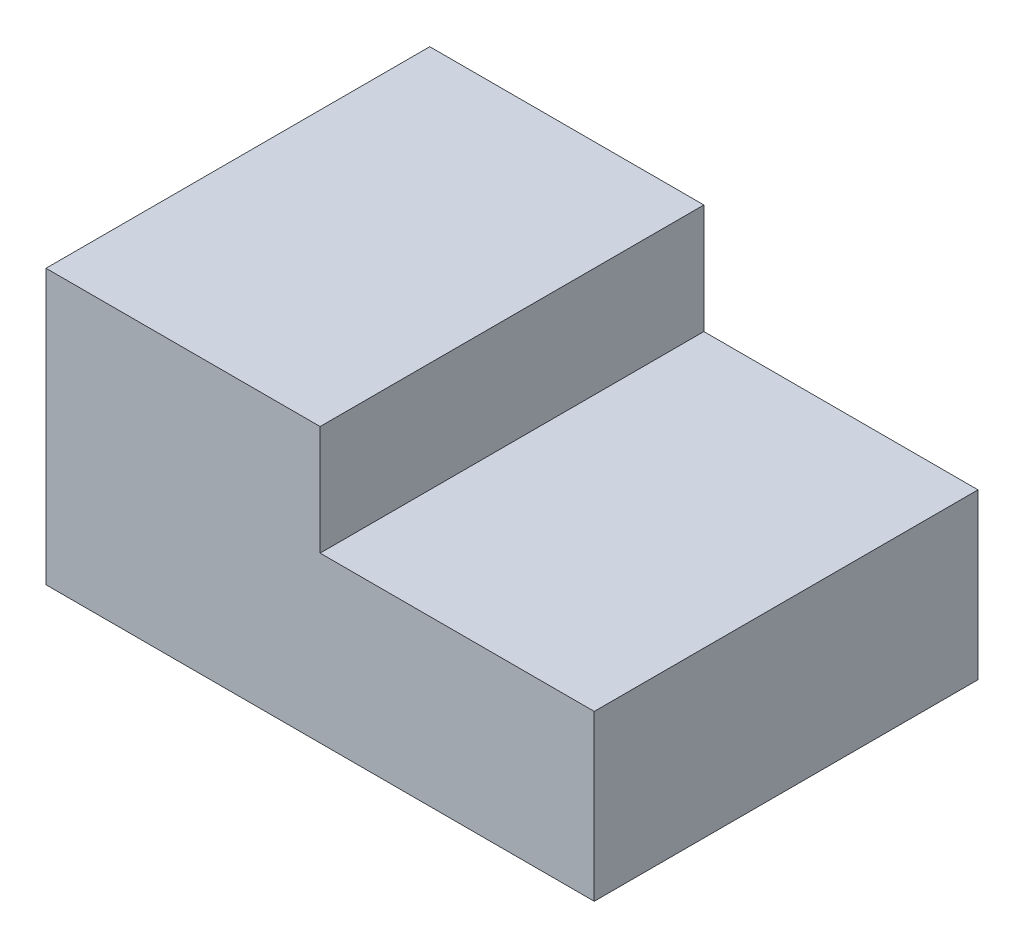
SolidWorks part; units mm, degrees
ref_plane "前视基准面" through (0, 0, 0) normal (0, 0, 1) x (1, 0, 0)
ref_plane "上视基准面" through (0, 0, 0) normal (0, 1, 0) x (1, 0, 0)
ref_plane "右视基准面" through (0, 0, 0) normal (1, 0, 0) x (0, 0, -1)
other "Configuration Table"
sketch "草图1" plane through (0, 0, 0) normal (0, 0, 1) x (1, 0, 0)
  line L0 (0, 0) -> (10, 0)
  line L1 (10, 0) -> (10, 3)
  line L2 (10, 3) -> (5, 3)
  line L3 (5, 3) -> (5, 5)
  line L4 (5, 5) -> (0, 5)
  line L5 (0, 5) -> (0, 0)
  dimension "D1" = 10
  dimension "D2" = 3
  dimension "D3" = 5
  dimension "D4" = 2
extrude "凸台-拉伸1" add sketch "草图1" along normal mid plane 7
sketch "草图2" plane through (0, 0, 0) normal (-1, 0, 0) x (0, 0, 1)
  line L0 (0, 0) -> (0, 2.5) construction
  line L1 (1.6, 4.1) -> (1.6, 0.9)
  line L2 (1.6, 4.1) -> (-1.6, 4.1)
  line L3 (1.6, 0.9) -> (-1.6, 0.9)
  line L4 (-1.6, 4.1) -> (-1.6, 0.9)
  line L5 (1.6, 4.1) -> (-1.6, 0.9) construction
  line L6 (1.6, 0.9) -> (-1.6, 4.1) construction
  dimension "D1" = 2.5
  dimension "D2" = 3.2
  dimension "D3" = 3.2
extrude "切除-拉伸1" cut sketch "草图2" against normal blind 3
sketch "草图3" plane through (0, 5, 0) normal (0, 1, 0) x (1, 0, 0)
  line L0 (0, 0) -> (1.5, 0) construction
  circle A0 centre (1.5, 0) radius 1
  dimension "D2" = 2
  dimension "D1" = 1.5
